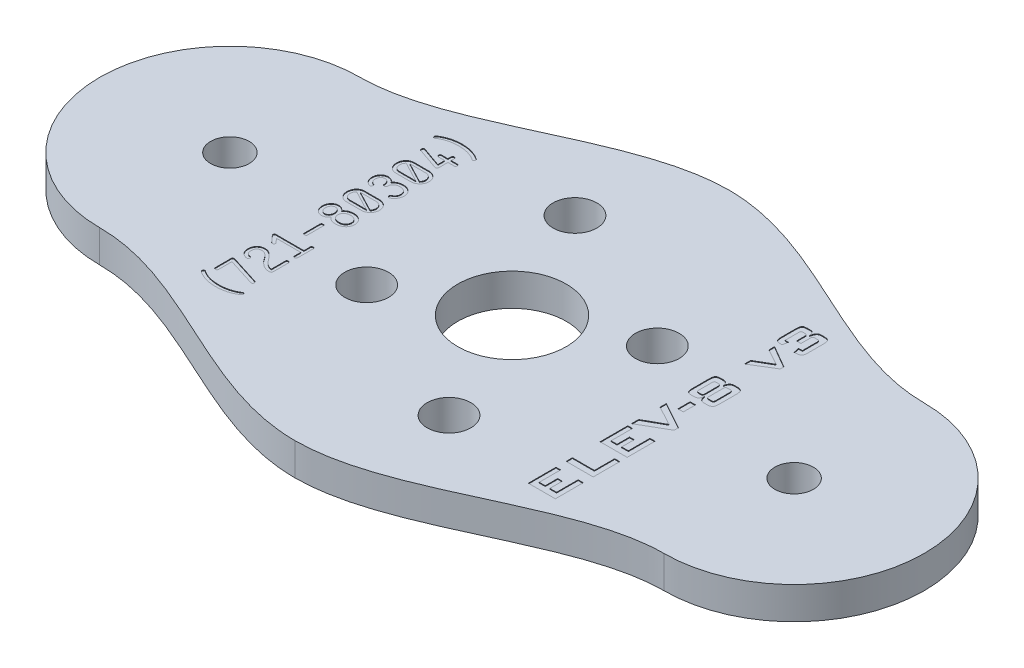
SolidWorks part; units mm, degrees
material "G-10/FR-4"
ref_plane "Front Plane" through (0, 0, 0) normal (0, 0, 1) x (1, 0, 0)
ref_plane "Top Plane" through (0, 0, 0) normal (0, 1, 0) x (1, 0, 0)
ref_plane "Right Plane" through (0, 0, 0) normal (1, 0, 0) x (0, 0, -1)
sketch "Sketch1" plane through (0, 0, 0) normal (0, 1, 0) x (1, 0, 0)
  line L0 (0, 24.8336) -> (0, -24.8336) construction
  line L1 (-20.6375, 0) -> (20.6375, 0) construction
  arc A1 (20.6375, -9.525) -> (20.6375, 9.525) centre (20.6375, 0) ccw
  circle A2 centre (0, 0) radius 15.875 construction
  arc A4 (-20.6375, -9.525) -> (-20.6375, 9.525) centre (-20.6375, 0) cw
  circle A5 centre (0, 0) radius 3.9688
  spline S0 degree 3 poles (20.6375, -9.525) (14.0921, -9.525) (6.9253, -15.875) (0, -15.875) knots 0 0 0 0 1 1 1 1
  spline S1 degree 3 poles (20.6375, 9.525) (14.0921, 9.525) (6.9253, 15.875) (0, 15.875) knots 0 0 0 0 1 1 1 1
  spline S2 degree 3 poles (-20.6375, -9.525) (-14.0921, -9.525) (-6.9253, -15.875) (0, -15.875) knots 0 0 0 0 1 1 1 1
  spline S3 degree 3 poles (-20.6375, 9.525) (-14.0921, 9.525) (-6.9253, 15.875) (0, 15.875) knots 0 0 0 0 1 1 1 1
  point P4 (0, 0)
  point P8 (0, 0)
  dimension "D1" = 19.05
  dimension "D3" = 31.75
  dimension "D5" = 7.9375
  dimension "D4" = 20.6375
extrude "Boss-Extrude1" add sketch "Sketch1" along normal blind 2.3622
hole_wizard "M3 Clearance Hole1" positions "Sketch2" profile "Sketch3" hole size "M3" standard "ANSI Metric" end condition through all
sketch "Sketch2" plane through (33.3375, 0, 0) normal (0, -1, 0) x (-1, 0, 0)
  point P0 (37.3629, 8.6326)
  point P1 (40.588, -3.3809)
  point P2 (29.3121, -8.6326)
  point P3 (26.087, 3.3809)
sketch "Sketch3" plane through (-4.0254, 0, -8.6326) normal (1, 0, 0) x (0, 0, -1)
  line L0 (0, 0) -> (0, 2.3622)
  line L1 (0, 2.3622) -> (1.6, 2.3622)
  line L2 (1.6, 2.3622) -> (1.6, 0)
  line L3 (1.6, 0) -> (0, 0)
  line L4 (0, -6.35) -> (0, 107.95) construction
  dimension "Thru Hole Dia." = 3.2
  dimension "Thru Hole Depth" = 2.3622
hole_wizard "#32 (0.116) Diameter Hole1" positions "Sketch7" profile "Sketch6" hole size "#32" standard "ANSI Inch" end condition through all
sketch "Sketch7" plane through (0, 0, 0) normal (0, -1, 0) x (-1, 0, 0)
  point P0 (-20.6375, 0)
  point P3 (20.6375, 0)
sketch "Sketch6" plane through (20.6375, 0, 0) normal (1, 0, 0) x (0, 0, -1)
  line L0 (0, 0) -> (0, 2.3622)
  line L1 (0, 2.3622) -> (1.4097, 2.3622)
  line L2 (1.4097, 2.3622) -> (1.4097, 0)
  line L5 (1.4097, 0) -> (0, 0)
  line L11 (0, -6.35) -> (0, 107.95) construction
  dimension "Thru Hole Dia." = 2.8194
  dimension "Thru Hole Depth" = 2.3622
sketch "Sketch8" plane through (0, 2.3622, 0) normal (0, 1, 0) x (1, 0, 0)
  line L0 (-11.43, -11.6201) -> (-11.43, 11.6201) construction
  line L1 (-4.0254, 8.6326) -> (7.2505, 3.3809) construction
  line L2 (-20.6375, 0) -> (20.6375, 0) construction
  line L3 (20.6375, 0) -> (-20.6375, 0) construction
  line L4 (13.208, 10.8171) -> (13.208, -10.8171) construction
  text T0 "(721-80304)" font "Parallax" height in points 8
  text T1 "ELEV-8 v3" font "BankGothic" height in points 7
  point P3 (-11.43, 0)
  point P17 (13.208, 0)
  dimension "D1" = 11.43
  dimension "D2" = 13.208
extrude "Raster Text" cut sketch "Sketch8" against normal blind 0.05
